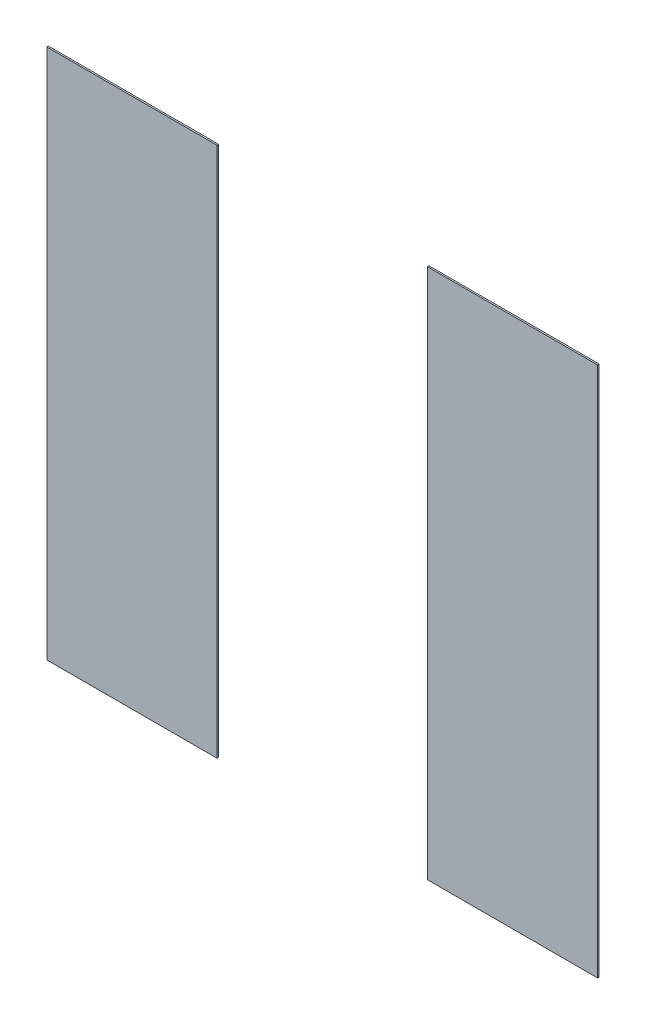
SolidWorks part; units mm, degrees
ref_plane "前视基准面" through (0, 0, 0) normal (0, 0, 1) x (1, 0, 0)
ref_plane "上视基准面" through (0, 0, 0) normal (0, 1, 0) x (1, 0, 0)
ref_plane "右视基准面" through (0, 0, 0) normal (1, 0, 0) x (0, 0, -1)
sketch "草图1" plane through (0, 0, 0) normal (0, 0, 1) x (1, 0, 0)
  line L1 (-3.4925, 3.3655) -> (-1.3335, 3.3655)
  line L2 (-3.4925, 3.3655) -> (-3.4925, -3.3655)
  line L3 (-3.4925, -3.3655) -> (-1.3335, -3.3655)
  line L4 (-1.3335, 3.3655) -> (-1.3335, -3.3655)
  line L5 (-3.4925, 3.3655) -> (-1.3335, -3.3655) construction
  line L6 (-3.4925, -3.3655) -> (-1.3335, 3.3655) construction
  line L7 (1.3335, 3.3655) -> (3.4925, 3.3655)
  line L8 (1.3335, 3.3655) -> (1.3335, -3.3655)
  line L9 (1.3335, -3.3655) -> (3.4925, -3.3655)
  line L10 (3.4925, 3.3655) -> (3.4925, -3.3655)
  line L11 (1.3335, 3.3655) -> (3.4925, -3.3655) construction
  line L12 (1.3335, -3.3655) -> (3.4925, 3.3655) construction
  point P0 (-2.413, 0)
  point P5 (2.413, 0)
  dimension "D1" = 3.3655
  dimension "D2" = 2.159
  dimension "D3" = 3.3655
  dimension "D4" = 2.159
extrude "凸台-拉伸1" add sketch "草图1" along normal blind 0.02
